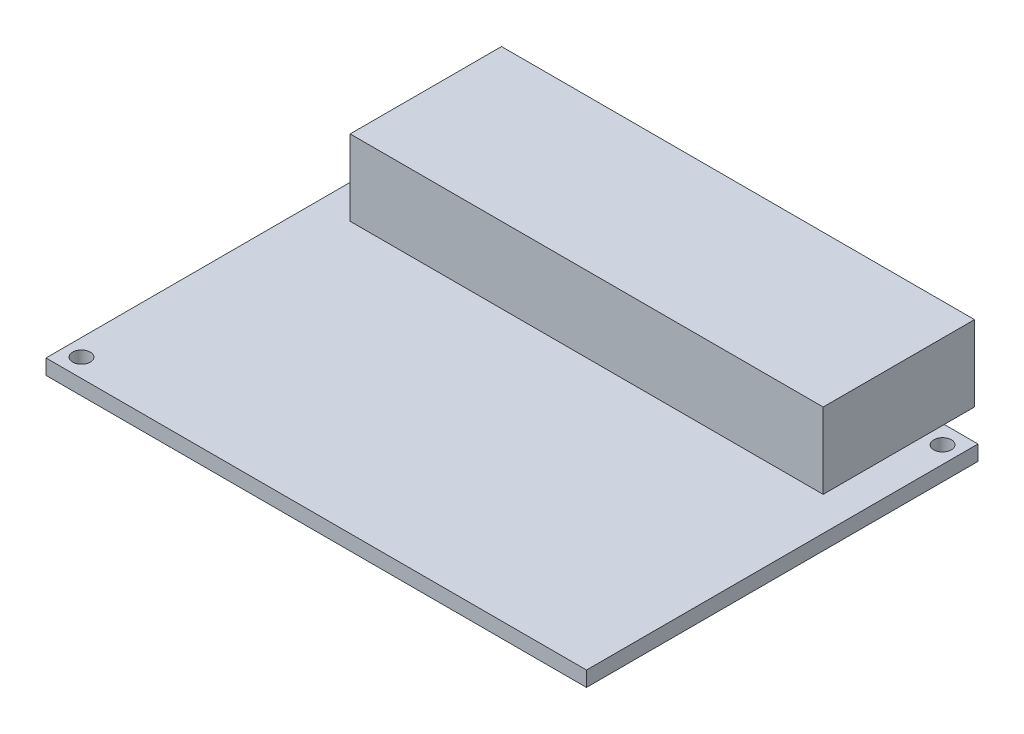
SolidWorks part; units mm, degrees
ref_plane "Front Plane" through (0, 0, 0) normal (0, 0, 1) x (1, 0, 0)
ref_plane "Top Plane" through (0, 0, 0) normal (0, 1, 0) x (1, 0, 0)
ref_plane "Right Plane" through (0, 0, 0) normal (1, 0, 0) x (0, 0, -1)
sketch "Sketch1" plane through (0, 0, 0) normal (0, 1, 0) x (1, 0, 0)
  line L1 (-45.35, -32.85) -> (45.35, -32.85)
  line L2 (-45.35, -32.85) -> (-45.35, 32.85)
  line L3 (-45.35, 32.85) -> (45.35, 32.85)
  line L4 (45.35, -32.85) -> (45.35, 32.85)
  line L5 (-45.35, -32.85) -> (45.35, 32.85) construction
  line L6 (-45.35, 32.85) -> (45.35, -32.85) construction
  line L7 (42.5, -29.75) -> (-42.5, -29.75) construction
  line L8 (42.5, -29.75) -> (42.5, 29.75) construction
  line L9 (42.5, 29.75) -> (-42.5, 29.75) construction
  line L10 (-42.5, -29.75) -> (-42.5, 29.75) construction
  line L11 (42.5, -29.75) -> (-42.5, 29.75) construction
  line L12 (42.5, 29.75) -> (-42.5, -29.75) construction
  circle A0 centre (-42.5, 29.75) radius 1.4732
  circle A1 centre (42.5, 29.75) radius 1.4732
  circle A2 centre (-42.5, -29.75) radius 1.4732
  point P0 (0, 0)
  point P6 (0, 0)
  dimension "D5" = 2.9464
  dimension "D1" = 59.5
  dimension "D2" = 85
  dimension "D3" = 90.7
  dimension "D4" = 65.7
extrude "Boss-Extrude1" add sketch "Sketch1" along normal blind 2.54 contours L2 L3 L4 L1
sketch "Sketch2" plane through (0, 2.54, 0) normal (0, 1, 0) x (1, 0, 0)
  line L0 (45.35, 32.85) -> (-45.35, 32.85) construction
  line L1 (39.6875, 12.53) -> (-39.6875, 12.53)
  line L2 (39.6875, 12.53) -> (39.6875, 37.93)
  line L3 (39.6875, 37.93) -> (-39.6875, 37.93)
  line L4 (-39.6875, 12.53) -> (-39.6875, 37.93)
  line L5 (39.6875, 12.53) -> (-39.6875, 37.93) construction
  line L6 (39.6875, 37.93) -> (-39.6875, 12.53) construction
  point P0 (0, 25.23)
  dimension "D1" = 5.08
  dimension "D2" = 79.375
  dimension "D3" = 25.4
extrude "Boss-Extrude2" add sketch "Sketch2" along normal blind 12.7
